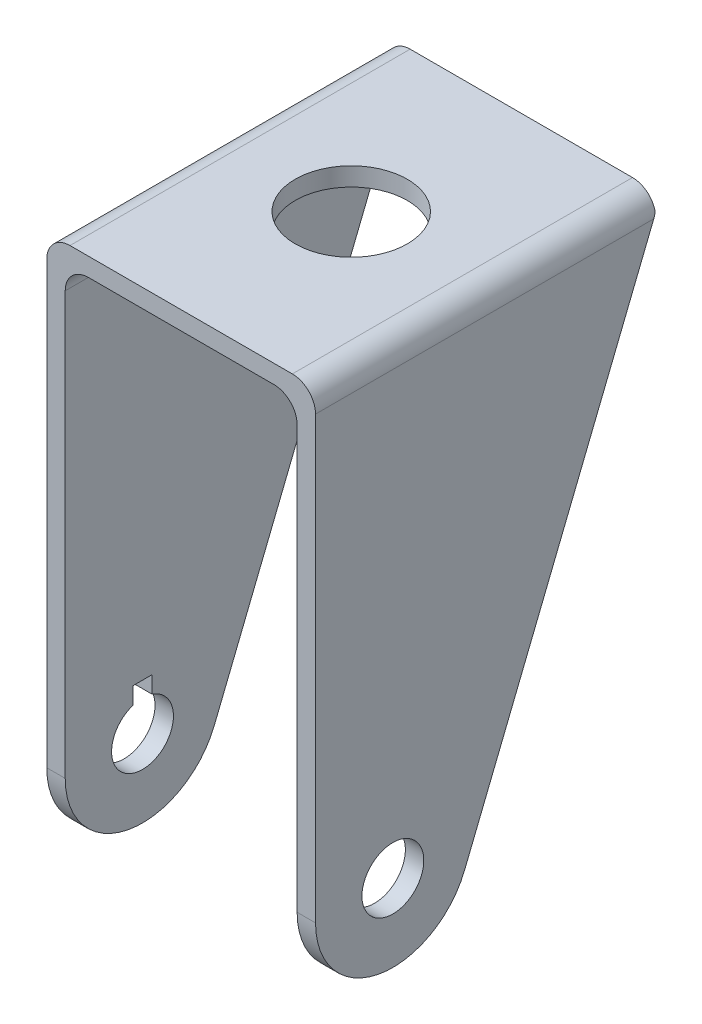
SolidWorks part; units mm, degrees
material "1023 Carbon Steel Sheet (SS)"
ref_plane "Front Plane" through (0, 0, 0) normal (0, 0, 1) x (1, 0, 0)
ref_plane "Top Plane" through (0, 0, 0) normal (0, 1, 0) x (1, 0, 0)
ref_plane "Right Plane" through (0, 0, 0) normal (1, 0, 0) x (0, 0, -1)
sketch "Sketch1" plane through (0, 0, 0) normal (0, 0, 1) x (1, 0, 0)
  line L0 (-15, 0) -> (15, 0) construction
  line L2 (-15, 60) -> (15, 60)
  line L3 (-15, 60) -> (-15, 57.6187)
  line L4 (-15, 57.6187) -> (15, 57.6187)
  line L5 (15, 60) -> (15, 57.6187)
  dimension "D1" = 30
  dimension "D2" = 2.3813
  dimension "D3" = 60
extrude "Top" add sketch "Sketch1" against normal blind 34 and the other way blind 10
sketch "Sketch2" plane through (15, 0, 0) normal (1, 0, 0) x (0, 0, -1)
  line L0 (-10, 60) -> (-10, 0)
  line L1 (34, 60) -> (34, 57.6187)
  line L2 (34, 57.6187) -> (9.2752, -3.7376)
  line L3 (-10, 60) -> (34, 60)
  circle A0 centre (0, 0) radius 10
  circle A1 centre (0, 0) radius 4
  line M2 (-10, 57.6187) -> (34, 57.6187)
  line M3 (34, 57.6187) -> (34, 60)
  line M4 (34, 60) -> (-10, 60)
  line M5 (-10, 60) -> (-10, 57.6187)
  dimension "D1" = 20
  dimension "D2" = 8
extrude "Side" add sketch "Sketch2" along normal blind 2.3813 contours A0 L2 L0 M2 | A0 A1 | M5 M2 M3 M4
mirror "Side Mirror" about plane through (0, 0, 0) normal (1, 0, 0) of "Side"
fillet "Top Fillets" radius 3 6 edges at (17.3813, 58.8094, -34) (17.3813, 60, -12) (-17.3813, 60, -12) (-17.3813, 58.8094, -34) (15, 57.6187, -12) (-15, 57.6187, -12)
sketch "Sketch3" plane through (0, 60, 0) normal (0, 1, 0) x (1, 0, 0)
  line L0 (0, 34) -> (0, -10) construction
  line L1 (14.3813, 34) -> (-14.3813, 34) construction
  line L2 (14.3813, -10) -> (-14.3813, -10) construction
  circle A0 centre (0, 12) radius 7.25
  dimension "D1" = 14.5
  dimension "D2" = 22
extrude "Top Hole" cut sketch "Sketch3" against normal through all
sketch "Sketch4" plane through (-17.3813, 0, 0) normal (-1, 0, 0) x (0, 0, 1)
  line L0 (0, 0) -> (0, 6) construction
  line L2 (-1.25, 6) -> (1.25, 6)
  line L3 (-1.25, 6) -> (-1.25, 0)
  line L4 (-1.25, 0) -> (1.25, 0)
  line L5 (1.25, 6) -> (1.25, 0)
  dimension "D1" = 2.5
  dimension "D2" = 6
extrude "Keyway" cut sketch "Sketch4" against normal up to next
